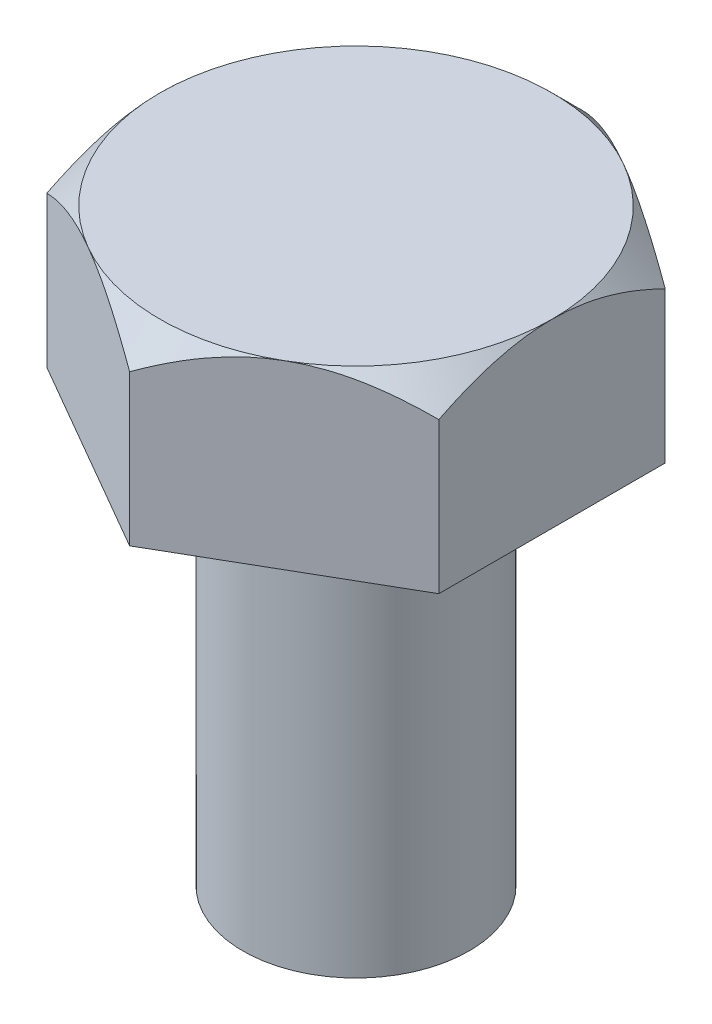
SolidWorks part; units mm, degrees
ref_plane "Front Plane" through (0, 0, 0) normal (0, 0, 1) x (1, 0, 0)
ref_plane "Top Plane" through (0, 0, 0) normal (0, 1, 0) x (1, 0, 0)
ref_plane "Right Plane" through (0, 0, 0) normal (1, 0, 0) x (0, 0, -1)
sketch "Sketch1" plane through (0, 0, 0) normal (0, 1, 0) x (1, 0, 0)
  line L1 (0, -5) -> (4.3301, -2.5)
  line L2 (4.3301, -2.5) -> (4.3301, 2.5)
  line L3 (4.3301, 2.5) -> (0, 5)
  line L4 (0, 5) -> (-4.3301, 2.5)
  line L5 (-4.3301, 2.5) -> (-4.3301, -2.5)
  line L6 (-4.3301, -2.5) -> (0, -5)
  circle A0 centre (0, 0) radius 4.3301 construction
  dimension "D1" = 10
extrude "Boss-Extrude1" add sketch "Sketch1" along normal blind 4
sketch "Sketch2" plane through (0, 0, 0) normal (0, -1, 0) x (1, 0, 0)
  circle A0 centre (0, 0) radius 2.5
  dimension "D1" = 5
extrude "Boss-Extrude2" add sketch "Sketch2" along normal blind 9
sketch "Sketch3" plane through (0, 4, 0) normal (0, 1, 0) x (1, 0, 0)
  circle A0 centre (0, 0) radius 4.3301
  dimension "D1" = 8.6603
extrude "Cut-Extrude1" cut sketch "Sketch3" against normal blind 9 draft 45 flip side to cut
